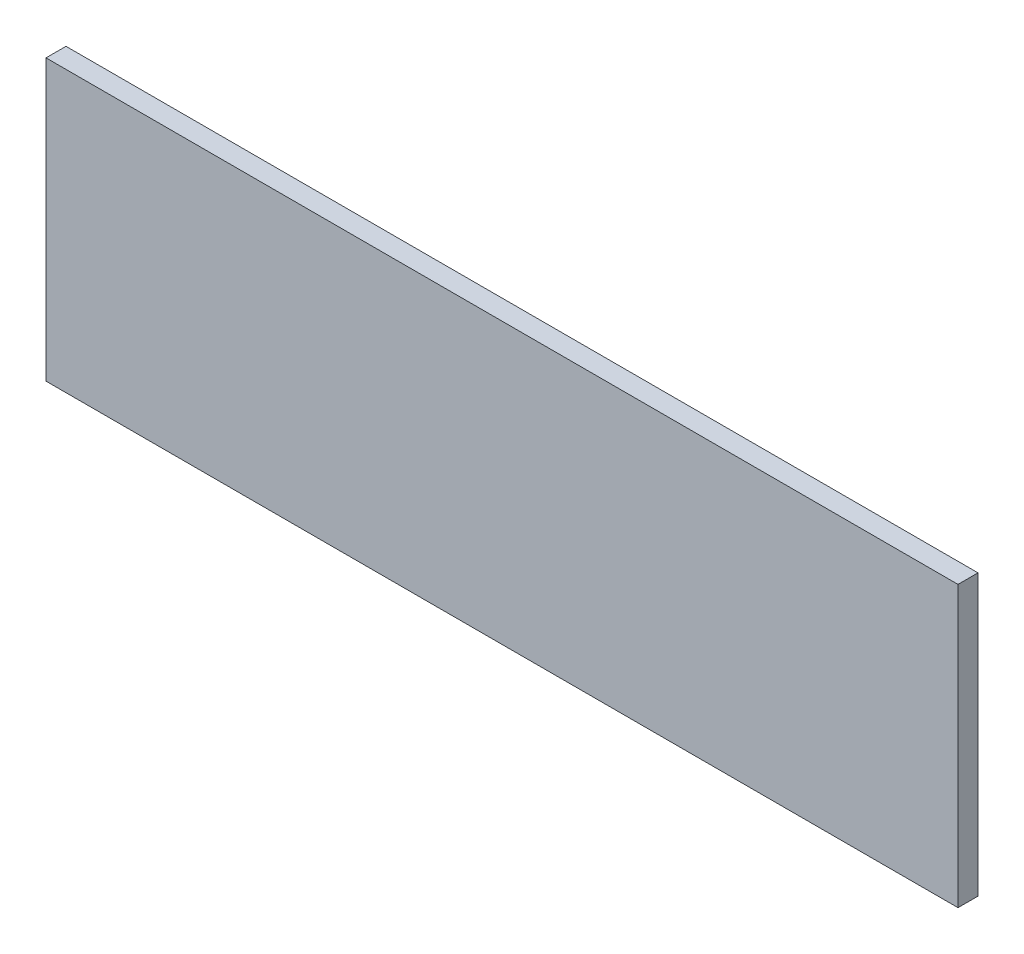
SolidWorks part; units mm, degrees
ref_plane "前视基准面" through (0, 0, 0) normal (0, 0, 1) x (1, 0, 0)
ref_plane "上视基准面" through (0, 0, 0) normal (0, 1, 0) x (1, 0, 0)
ref_plane "右视基准面" through (0, 0, 0) normal (1, 0, 0) x (0, 0, -1)
sketch "草图1" plane through (0, 0, 0) normal (0, 0, 1) x (1, 0, 0)
  line L1 (114, -35) -> (-114, -35)
  line L2 (114, -35) -> (114, 35)
  line L3 (114, 35) -> (-114, 35)
  line L4 (-114, -35) -> (-114, 35)
  line L5 (114, -35) -> (-114, 35) construction
  line L6 (114, 35) -> (-114, -35) construction
  point P0 (0, 0)
  dimension "D1" = 228
  dimension "D2" = 70
extrude "凸台-拉伸1" add sketch "草图1" along normal blind 5
